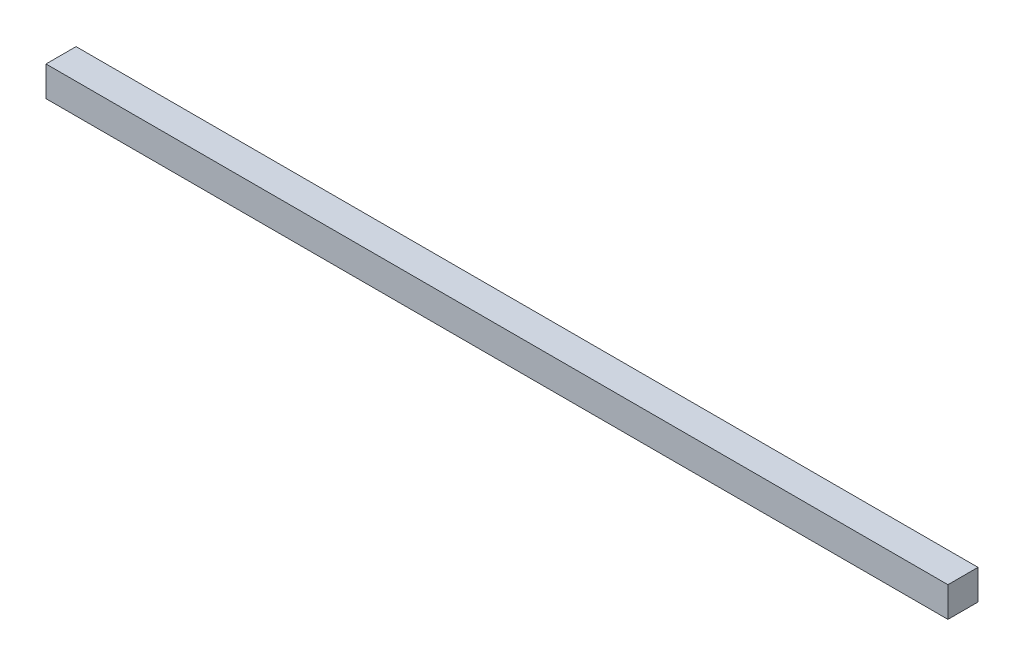
SolidWorks part; units mm, degrees
ref_plane "Front Plane" through (0, 0, 0) normal (0, 0, 1) x (1, 0, 0)
ref_plane "Top Plane" through (0, 0, 0) normal (0, 1, 0) x (1, 0, 0)
ref_plane "Right Plane" through (0, 0, 0) normal (1, 0, 0) x (0, 0, -1)
sketch "Sketch1" plane through (0, 0, 0) normal (1, 0, 0) x (0, 0, -1)
  line L1 (0, 0) -> (25.4, 0)
  line L2 (0, 0) -> (0, -25.4)
  line L3 (0, -25.4) -> (25.4, -25.4)
  line L4 (25.4, 0) -> (25.4, -25.4)
  dimension "D1" = 25.4
  dimension "D2" = 25.4
extrude "Boss-Extrude1" add sketch "Sketch1" along normal blind 762 contours L1 L4 L3 L2
